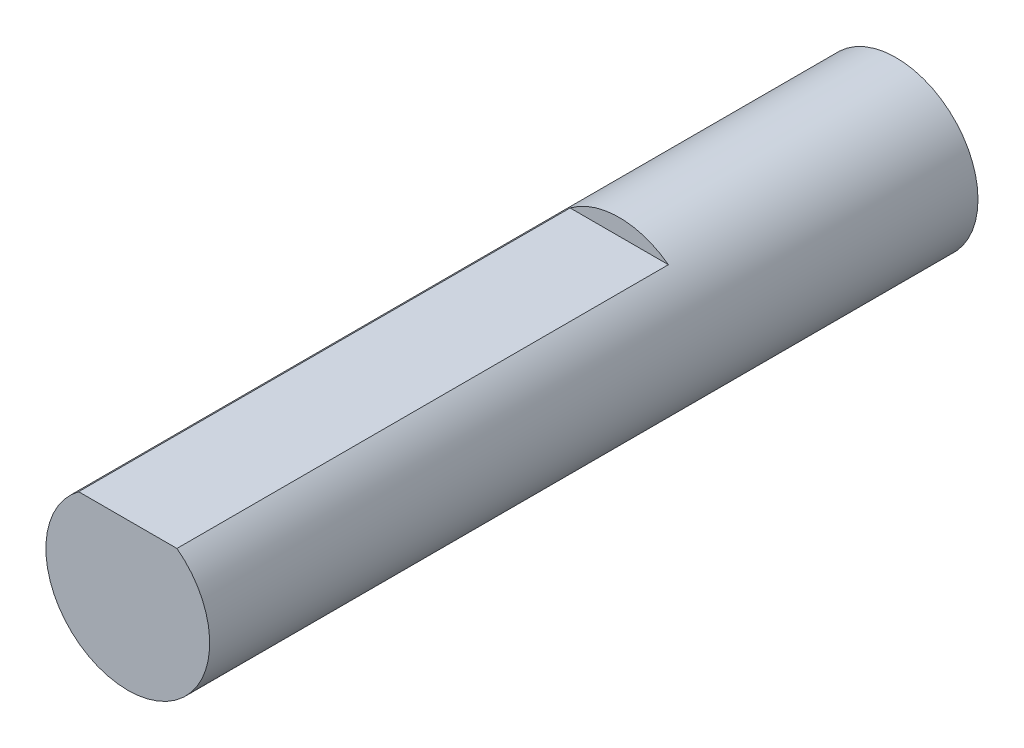
SolidWorks part; units mm, degrees
ref_plane "Front Plane" through (0, 0, 0) normal (0, 0, 1) x (1, 0, 0)
ref_plane "Top Plane" through (0, 0, 0) normal (0, 1, 0) x (1, 0, 0)
ref_plane "Right Plane" through (0, 0, 0) normal (1, 0, 0) x (0, 0, -1)
sketch "Sketch1" plane through (0, 0, 0) normal (0, 0, 1) x (1, 0, 0)
  circle A0 centre (0, 0) radius 2.5
extrude "Boss-Extrude1" add sketch "Sketch1" along normal blind 23.45
sketch "Sketch2" plane through (0, 0, 23.45) normal (0, 0, 1) x (1, 0, 0)
  line L0 (1.5, 2) -> (-1.5, 2)
  circle A0 centre (0, 0) radius 2.5 construction
  circle A1 centre (0, 0) radius 2.5031
  circle M2 centre (0, 0) radius 2.5
  dimension "D1" = 3
extrude "Cut-Extrude1" cut sketch "Sketch2" against normal blind 15 contours L0 M2
